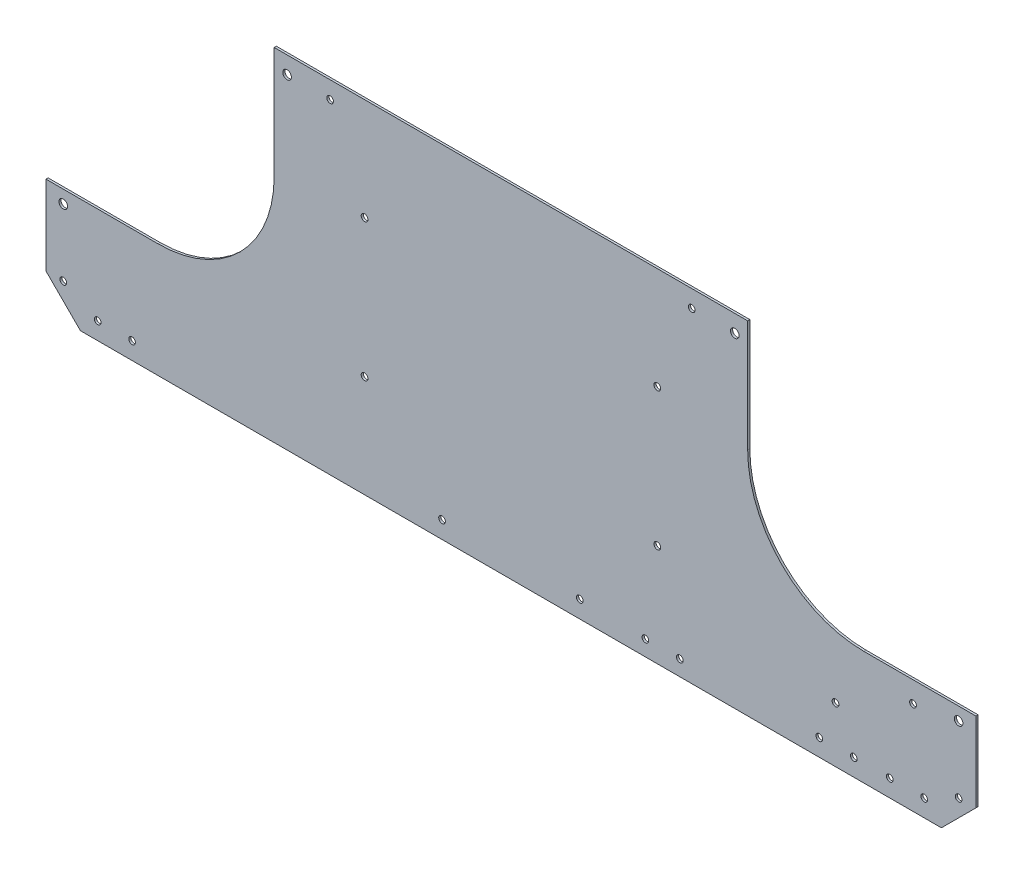
SolidWorks part; units mm, degrees
material "Perspex (TM) GS Acrylic Cast Sheet"
ref_plane "Front Plane" through (0, 0, 0) normal (0, 0, 1) x (1, 0, 0)
ref_plane "Top Plane" through (0, 0, 0) normal (0, 1, 0) x (1, 0, 0)
ref_plane "Right Plane" through (0, 0, 0) normal (1, 0, 0) x (0, 0, -1)
sketch "Sketch1" plane through (0, 0, 0) normal (0, 0, 1) x (1, 0, 0)
  line L1 (-457.2, -304.8) -> (457.2, -304.8)
  line L2 (-457.2, -304.8) -> (-457.2, 304.8)
  line L3 (-457.2, 304.8) -> (457.2, 304.8)
  line L4 (457.2, -304.8) -> (457.2, 304.8)
  line L5 (0, 304.8) -> (0, -304.8) construction
  line L6 (-457.2, 0) -> (457.2, 0) construction
  point P0 (0, 0)
  point P4 (-320.04, 0)
  point P5 (320.04, 0)
  point P6 (0, 213.36)
  point P7 (0, -213.36)
  dimension "Length" = 914.4
  dimension "Width" = 609.6
  dimension "Break" = 137.16
  dimension "D2" = 137.16
  dimension "D1" = 91.44
  dimension "D3" = 91.44
sketch "Sketch2" plane through (0, 0, 0) normal (1, 0, 0) x (0, 0, -1)
  line L0 (-0.7938, -304.8) -> (0.7938, -304.8)
  dimension "Thickness" = 1.5875
sketch "Sketch3" plane through (0, 0, 0) normal (0, 0, 1) x (1, 0, 0)
  line L0 (-457.2, -304.8) -> (-457.2, 304.8) construction
  line L1 (-457.2, -304.8) -> (457.2, -304.8) construction
  line L2 (457.2, -304.8) -> (457.2, 304.8) construction
  line L3 (-457.2, 304.8) -> (457.2, 304.8) construction
  line L4 (-457.2, -304.8) -> (-457.2, 304.8)
  line L5 (-457.2, -304.8) -> (457.2, -304.8)
  line L6 (457.2, -304.8) -> (457.2, 304.8)
  line L7 (-457.2, 304.8) -> (457.2, 304.8)
extrude "Boss-Extrude1" add sketch "Sketch3" along normal mid plane 1.5875
sketch "Sketch4" plane through (0, 0, 0.7937) normal (0, 0, 1) x (1, 0, 0)
  line L5 (-326.7349, -279.5815) -> (-352.1349, -254.1815)
  line L12 (308.2651, -279.5815) -> (333.6651, -254.1815)
  line L19 (-352.1349, -254.1815) -> (-352.1349, -29.709)
  line L20 (-349.5949, -27.169) -> (331.1251, -27.169)
  line L21 (-326.7349, -279.5815) -> (308.2651, -279.5815)
  line L22 (308.2651, -27.169) -> (308.2651, -687.569) construction
  line L23 (308.2651, -279.5815) -> (-326.7349, -279.5815) construction
  line L26 (333.6651, -254.1815) -> (333.6651, -29.709)
  arc A0 (333.6651, -29.709) -> (331.1251, -27.169) centre (331.1251, -29.709) ccw
  arc A1 (-349.5949, -27.169) -> (-352.1349, -29.709) centre (-349.5949, -29.709) ccw
  point P20 (333.6651, -27.169)
  point P23 (-352.1349, -27.169)
  dimension "D1" = 2.54
  dimension "D2" = 2.54
extrude "Cut-Extrude1" cut sketch "Sketch4" against normal blind 2.54 flip side to cut
sketch "Sketch7" plane through (0, 0, 0.7937) normal (0, 0, 1) x (1, 0, 0)
  line L6 (-269.5849, -173.219) -> (-352.1349, -173.219) construction
  line L18 (-352.1349, -712.969) -> (-352.1349, -52.569) construction
  line L24 (-352.1349, -173.219) -> (-352.1349, -27.169) construction
  line L25 (-206.0849, -109.719) -> (-206.0849, -27.169) construction
  line L26 (-352.1349, -27.169) -> (308.2651, -27.169) construction
  line L27 (-206.0849, -27.169) -> (-352.1349, -27.169) construction
  line L28 (-269.5849, -195.444) -> (-374.3599, -195.444)
  line L29 (-374.3599, -195.444) -> (-374.3599, -4.944)
  line L30 (-183.8599, -4.944) -> (-374.3599, -4.944)
  line L31 (-183.8599, -109.719) -> (-183.8599, -4.944)
  arc A5 (-206.0849, -109.719) -> (-269.5849, -173.219) centre (-269.5849, -109.719) cw construction
  arc A6 (-183.8599, -109.719) -> (-269.5849, -195.444) centre (-269.5849, -109.719) cw
  dimension "D1" = 22.225
extrude "Cut-Extrude2" cut sketch "Sketch7" against normal blind 2.54
sketch "Sketch8" plane through (0, 0, 0.7937) normal (0, 0, 1) x (1, 0, 0)
  line L18 (187.6151, -109.719) -> (187.6151, -27.169) construction
  line L19 (-352.1349, -27.169) -> (308.2651, -27.169) construction
  line L20 (187.6151, -27.169) -> (333.6651, -27.169) construction
  line L21 (251.1151, -173.219) -> (333.6651, -173.219) construction
  line L22 (333.6651, -27.169) -> (333.6651, -687.569) construction
  line L23 (333.6651, -173.219) -> (333.6651, -27.169) construction
  line L24 (251.1151, -195.444) -> (355.8901, -195.444)
  line L25 (355.8901, -195.444) -> (355.8901, -4.944)
  line L26 (165.3901, -4.944) -> (355.8901, -4.944)
  line L27 (165.3901, -109.719) -> (165.3901, -4.944)
  arc A4 (187.6151, -109.719) -> (251.1151, -173.219) centre (251.1151, -109.719) ccw construction
  arc A5 (165.3901, -109.719) -> (251.1151, -195.444) centre (251.1151, -109.719) ccw
  dimension "D1" = 22.225
extrude "Cut-Extrude3" cut sketch "Sketch8" against normal blind 2.54
sketch "Sketch9" plane through (0, 0, 0.7937) normal (0, 0, 1) x (1, 0, 0)
  point P0 (-339.4349, -254.1815)
  point P1 (-314.0349, -266.8815)
  point P3 (-288.6349, -266.8815)
  point P5 (-339.4349, -204.969)
  point P7 (89.9521, -268.1131)
  point P9 (115.3521, -268.1131)
  point P11 (218.2221, -266.8815)
  point P13 (243.6221, -266.8815)
  point P15 (270.1651, -266.8815)
  point P17 (295.5651, -266.8815)
  point P19 (320.9651, -254.1815)
  point P21 (320.9651, -204.969)
  point P23 (-142.5849, -39.869)
  point P25 (124.1151, -39.869)
hole_wizard "#10 (0.1935) Diameter Hole1" positions "Sketch10" profile "Sketch11" hole size "#10" standard "ANSI Inch" end condition through all
sketch "Sketch10" plane through (0, 0, 0.7937) normal (0, 0, 1) x (1, 0, 0)
  point P0 (-288.6349, -266.8815)
  point P3 (-314.0349, -266.8815)
  point P6 (-339.4349, -254.1815)
  point P9 (89.9521, -268.1131)
  point P12 (115.3521, -268.1131)
  point P15 (218.2221, -266.8815)
  point P18 (243.6221, -266.8815)
  point P21 (295.5651, -266.8815)
  point P24 (270.1651, -266.8815)
  point P27 (320.9651, -254.1815)
  point P31 (124.1151, -39.869)
  point P34 (-142.5849, -39.869)
  point P37 (-60.0349, -266.8815)
  point P40 (41.5651, -266.8815)
sketch "Sketch11" plane through (-288.6349, -266.8815, 0.7937) normal (1, 0, 0) x (0, -1, 0)
  line L0 (0, 0) -> (0, 1.5875)
  line L1 (0, 1.5875) -> (2.4574, 1.5875)
  line L2 (2.4574, 1.5875) -> (2.4574, 0)
  line L5 (2.4574, 0) -> (0, 0)
  line L11 (0, -6.35) -> (0, 107.95) construction
  dimension "Thru Hole Dia." = 4.9149
  dimension "Thru Hole Depth" = 1.5875
hole_wizard "1/4 (0.25) Diameter Hole1" positions "Sketch12" profile "Sketch13" hole size "1/4" standard "ANSI Inch" end condition through all
sketch "Sketch12" plane through (0, 0, 0.7937) normal (0, 0, 1) x (1, 0, 0)
  point P0 (-339.4349, -204.969)
  point P3 (320.9651, -204.969)
  point P7 (155.8651, -39.869)
  point P10 (-174.3349, -39.869)
sketch "Sketch13" plane through (-339.4349, -204.969, 0.7937) normal (1, 0, 0) x (0, -1, 0)
  line L0 (0, 0) -> (0, 1.5875)
  line L1 (0, 1.5875) -> (3.175, 1.5875)
  line L2 (3.175, 1.5875) -> (3.175, 0)
  line L5 (3.175, 0) -> (0, 0)
  line L11 (0, -6.35) -> (0, 107.95) construction
  dimension "Thru Hole Dia." = 6.35
  dimension "Thru Hole Depth" = 1.5875
hole_wizard "#10 Clearance Hole1" positions "Sketch14" profile "Sketch15" hole size "#10" standard "ANSI Inch" end condition through all
sketch "Sketch14" plane through (0, 0, 0.7937) normal (0, 0, 1) x (1, 0, 0)
  point P0 (-117.1849, -204.1753)
  point P3 (-117.1849, -102.5753)
  point P6 (98.7151, -102.5753)
  point P9 (98.7151, -204.1753)
  point P13 (230.1601, -238.7828)
  point P16 (287.3101, -210.8428)
  point P19 (0, 0)
  point P20 (230.1601, -238.7828)
  point P22 (0, 0)
  point P23 (287.3101, -210.8428)
  point P25 (-117.1849, -204.1753)
  point P27 (-117.1849, -102.5753)
  point P29 (0, 0)
  point P30 (98.7151, -102.5753)
  point P32 (98.7151, -204.1753)
sketch "Sketch15" plane through (-117.1849, -204.1753, 0.7937) normal (1, 0, 0) x (0, -1, 0)
  line L0 (0, 0) -> (0, 1.5875)
  line L1 (0, 1.5875) -> (2.4892, 1.5875)
  line L2 (2.4892, 1.5875) -> (2.4892, 0)
  line L5 (2.4892, 0) -> (0, 0)
  line L11 (0, -6.35) -> (0, 107.95) construction
  dimension "Thru Hole Dia." = 4.9784
  dimension "Thru Hole Depth" = 1.5875
equation "\"D1@Boss-Extrude1\"=\"thickness@sketch2\""
equation "\"Break@Sketch1\" = \"Length@Sketch1\" * 0.15"
equation "\"D2@Sketch1\" = \"Break@Sketch1\""
equation "\"D1@Sketch1\"=\"Width@Sketch1\"*0.15"
equation "\"D3@Sketch1\"=\"D1@Sketch1\""
